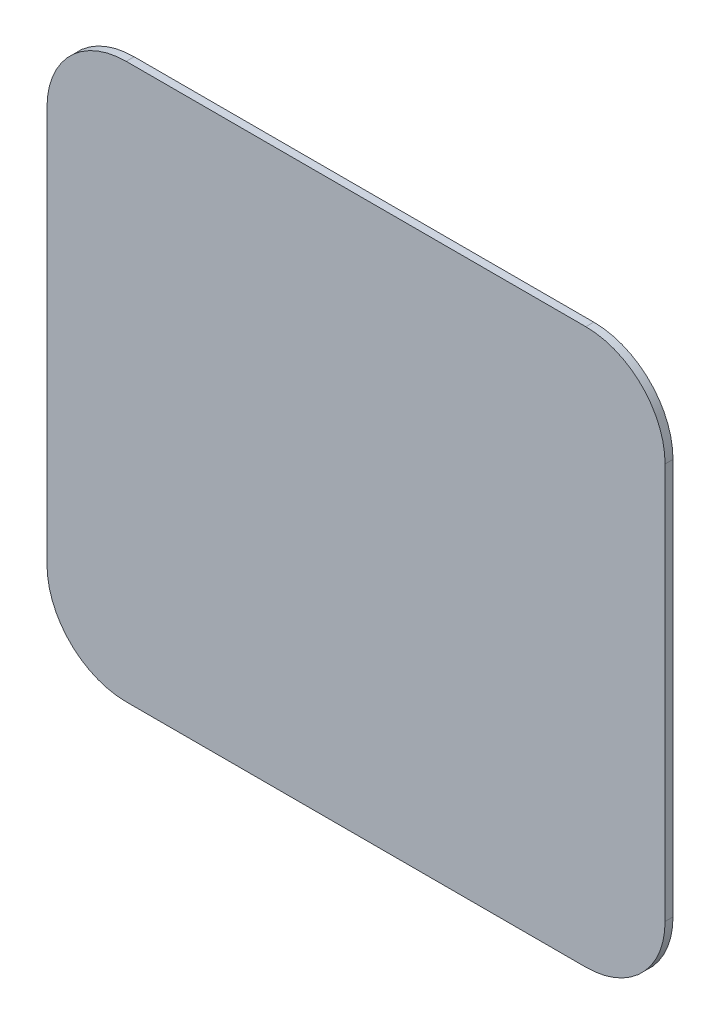
SolidWorks part; units mm, degrees
ref_plane "Front Plane" through (0, 0, 0) normal (0, 0, 1) x (1, 0, 0)
ref_plane "Top Plane" through (0, 0, 0) normal (0, 1, 0) x (1, 0, 0)
ref_plane "Right Plane" through (0, 0, 0) normal (1, 0, 0) x (0, 0, -1)
sketch "Sketch1" plane through (0, 0, 0) normal (0, 0, 1) x (1, 0, 0)
  line L0 (85.3333, 256) -> (81.5286, 231.264) construction
  line L1 (-153.9588, 7.6106) -> (187.3745, 7.6106) construction
  line L7 (-39.0754, 39.9502) -> (38.9246, 39.9502)
  line L8 (-39.0754, 39.9502) -> (-39.0754, -30.0498)
  line L9 (-39.0754, -30.0498) -> (38.9246, -30.0498)
  line L10 (38.9246, 39.9502) -> (38.9246, -30.0498)
  point P0 (0, 0)
  point P6 (0, 0)
  dimension "D1" = 78
  dimension "D2" = 70
extrude "Boss-Extrude1" add sketch "Sketch1" along normal blind 1
fillet "Fillet1" radius 10 4 edges at (-39.0754, 39.9502, 0.5) (-39.0754, -30.0498, 0.5) (38.9246, -30.0498, 0.5) (38.9246, 39.9502, 0.5)
sketch "Sketch2" plane through (0, 0, 0) normal (0, 0, -1) x (-1, 0, 0)
  line L0 (-28.9246, 39.9502) -> (29.0754, 39.9502) construction
  line L1 (29.0754, -30.0498) -> (-28.9246, -30.0498) construction
  line L2 (39.0754, 29.9502) -> (39.0754, -20.0498) construction
  line L3 (-38.9246, -20.0498) -> (-38.9246, 29.9502) construction
  line L4 (0.0754, 4.9502) -> (32.5754, -27.5498) construction
  line L5 (0.0754, 4.9502) -> (32.5754, 37.4502) construction
  line L6 (0.0754, 4.9502) -> (-32.4246, 37.4502) construction
  line L7 (0.0754, 4.9502) -> (-32.4246, -27.5498) construction
  line L8 (32.5754, 37.4502) -> (32.5754, -27.5498) construction
  line L9 (32.5754, -27.5498) -> (-32.4246, -27.5498) construction
  line L10 (-32.4246, -27.5498) -> (-32.4246, 37.4502) construction
  line L11 (-32.4246, 37.4502) -> (32.5754, 37.4502) construction
  line L12 (-21.1378, 26.1634) -> (-17.6023, 22.6279)
  line L13 (-21.1378, -16.263) -> (-17.6023, -12.7275)
  line L14 (21.2886, 26.1634) -> (17.7531, 22.6279)
  line L15 (12.4498, 17.3246) -> (8.9142, 13.789)
  line L16 (8.9142, 13.789) -> (8.9228, 13.8599)
  line L17 (21.2886, -16.263) -> (17.7531, -12.7275)
  line L18 (12.4498, -7.4242) -> (8.9142, -3.8886)
  line L19 (0.0754, 4.9502) -> (0.0754, 39.9502) construction
  line L20 (0.0754, 39.9502) -> (0.0754, -30.0498) construction
  line L21 (-12.299, 17.3246) -> (-8.7634, 13.789)
  line L22 (-12.299, -7.4242) -> (-8.7634, -3.8886)
  circle A0 centre (0.0754, 4.9502) radius 5
  arc A1 (8.9142, -3.8886) -> (8.9142, 13.789) centre (0.0754, 4.9502) ccw
  arc A2 (12.4498, -7.4242) -> (12.4498, 17.3246) centre (0.0754, 4.9502) ccw
  arc A3 (17.7531, -12.7275) -> (17.7531, 22.6279) centre (0.0754, 4.9502) ccw
  arc A4 (21.2886, -16.263) -> (21.2886, 26.1634) centre (0.0754, 4.9502) ccw
  arc A5 (-21.1378, -16.263) -> (-21.1378, 26.1634) centre (0.0754, 4.9502) cw
  arc A6 (-17.6023, -12.7275) -> (-17.6023, 22.6279) centre (0.0754, 4.9502) cw
  arc A7 (-12.299, -7.4242) -> (-12.299, 17.3246) centre (0.0754, 4.9502) cw
  arc A8 (-8.7634, -3.8886) -> (-8.7634, 13.789) centre (0.0754, 4.9502) cw
  point P26 (12.5754, 4.9502)
  point P27 (17.5754, 4.9502)
  point P28 (25.0754, 4.9502)
  point P29 (30.0754, 4.9502)
  dimension "D15" = 10
  dimension "D17" = 17.5
  dimension "D1" = 35
  dimension "D2" = 39
  dimension "D3" = 35
  dimension "D4" = 39
  dimension "D5" = 90
  dimension "D6" = 90
  dimension "D7" = 90
  dimension "D8" = 90
  dimension "D9" = 90
  dimension "D10" = 90
  dimension "D11" = 90
  dimension "D12" = 90
  dimension "D13" = 65
  dimension "D14" = 65
  dimension "D16" = 12.5
  dimension "D18" = 25
  dimension "D19" = 30
extrude "Boss-Extrude3" add sketch "Sketch2" along normal blind 1 contours L18 A2 L15 A1 | A0 | L17 A4 L14 A3 | L22 A8 L21 A7 | L13 A6 L12 A5
